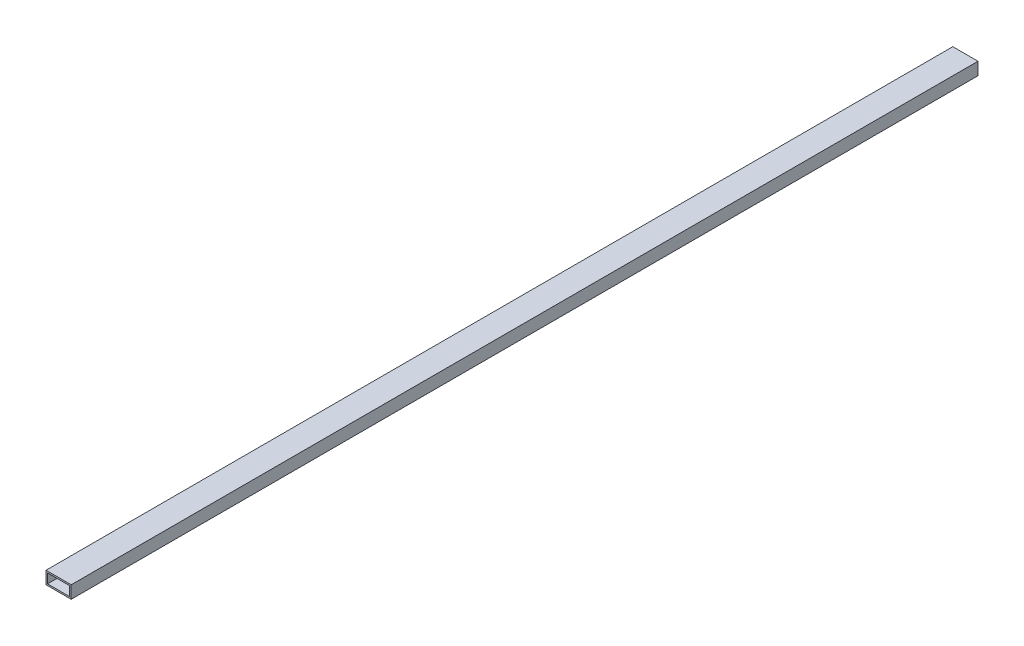
SolidWorks part; units mm, degrees
ref_plane "Front Plane" through (0, 0, 0) normal (0, 0, 1) x (1, 0, 0)
ref_plane "Top Plane" through (0, 0, 0) normal (0, 1, 0) x (1, 0, 0)
ref_plane "Right Plane" through (0, 0, 0) normal (1, 0, 0) x (0, 0, -1)
sketch "Sketch1" plane through (0, 0, 0) normal (0, 0, 1) x (1, 0, 0)
  line L0 (-11.1125, 4.7625) -> (11.1125, 4.7625)
  line L2 (-12.7, 6.35) -> (12.7, 6.35)
  line L3 (-12.7, 6.35) -> (-12.7, -6.35)
  line L4 (-12.7, -6.35) -> (12.7, -6.35)
  line L5 (12.7, 6.35) -> (12.7, -6.35)
  line L10 (11.1125, 4.7625) -> (11.1125, -4.7625)
  line L11 (-11.1125, -4.7625) -> (11.1125, -4.7625)
  line L12 (-11.1125, 4.7625) -> (-11.1125, -4.7625)
  point P12 (0, 6.35)
  point P14 (12.7, 0)
  dimension "Wall Thickness" = 1.5875
  dimension "Outside Width" = 25.4
  dimension "Outside Height" = 12.7
  dimension "Inside Height" = 9.525
  dimension "Inside Width" = 22.225
sketch "Sketch2" plane through (0, 0, 0) normal (1, 0, 0) x (0, 0, -1)
  line L0 (457.2, 0) -> (-457.2, 0)
  point P4 (0, 0)
  point P7 (-457.2, 0)
  point P10 (457.2, 0)
  dimension "Length" = 914.4
sketch "Sketch3" plane through (0, 0, 0) normal (0, 0, 1) x (1, 0, 0)
  line L21 (12.7, 6.35) -> (-12.7, 6.35)
  line L22 (12.7, -6.35) -> (12.7, 6.35)
  line L23 (-12.7, -6.35) -> (12.7, -6.35)
  line L24 (-12.7, 6.35) -> (-12.7, -6.35)
  line L25 (12.7, 6.35) -> (-12.7, 6.35)
  line L26 (12.7, -6.35) -> (12.7, 6.35)
  line L27 (-12.7, -6.35) -> (12.7, -6.35)
  line L28 (-12.7, 6.35) -> (-12.7, -6.35)
  line L29 (11.1125, 4.7625) -> (-11.1125, 4.7625)
  line L30 (11.1125, -4.7625) -> (11.1125, 4.7625)
  line L31 (-11.1125, -4.7625) -> (11.1125, -4.7625)
  line L32 (-11.1125, 4.7625) -> (-11.1125, -4.7625)
  line L33 (11.1125, 4.7625) -> (-11.1125, 4.7625)
  line L34 (11.1125, -4.7625) -> (11.1125, 4.7625)
  line L35 (-11.1125, -4.7625) -> (11.1125, -4.7625)
  line L36 (-11.1125, 4.7625) -> (-11.1125, -4.7625)
  dimension "D1" = 0
  dimension "D2" = 0
extrude "Boss-Extrude1" add sketch "Sketch3" along normal up to vertex (457.2 mm away) and the other way up to vertex (457.2 mm away) up to point (0, 0, 457.2) other way up to point (0, 0, -457.2)
sketch "Drawing Reference" plane through (0, 0, 0) normal (1, 0, 0) x (0, 0, -1)
  line L0 (-457.2, 0) -> (457.2, 0) construction
  line L1 (0, -6.35) -> (0, 6.35) construction
  line L2 (-457.2, -6.35) -> (457.2, -6.35) construction
  line L5 (-457.2, 6.35) -> (457.2, 6.35) construction
  point P7 (-438.912, 0)
  point P8 (438.912, 0)
  dimension "D1" = 18.288
equation "\"D1@Drawing Reference\"=\"Outside Width@Sketch1\" * 0.72"
